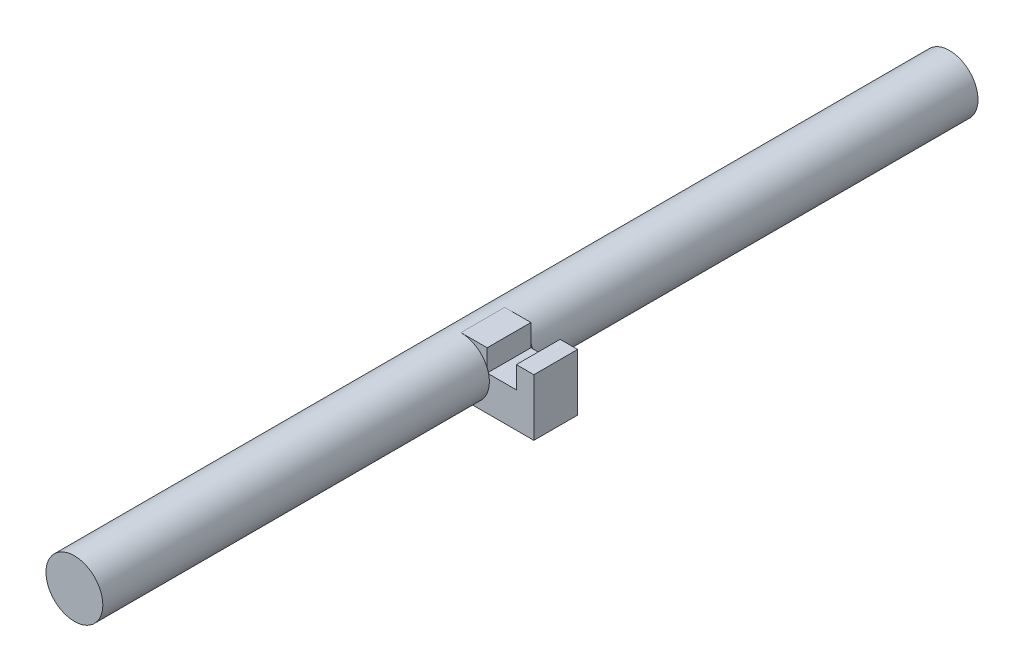
SolidWorks part; units mm, degrees
ref_plane "前视基准面" through (0, 0, 0) normal (0, 0, 1) x (1, 0, 0)
ref_plane "上视基准面" through (0, 0, 0) normal (0, 1, 0) x (1, 0, 0)
ref_plane "右视基准面" through (0, 0, 0) normal (1, 0, 0) x (0, 0, -1)
sketch "草图1" plane through (0, 0, 0) normal (0, 0, 1) x (1, 0, 0)
  circle A0 centre (0, 0) radius 1.95
  dimension "D1" = 3.9
extrude "凸台-拉伸1" add sketch "草图1" along normal blind 60
sketch "Sketch1" plane through (0, 0, 0) normal (1, 0, 0) x (0, 0, -1)
  line L0 (0, 1.95) -> (-60, 1.95) construction
  line L1 (-33.5, 1.95) -> (-30.5, 1.95)
  line L2 (-33.5, 1.95) -> (-33.5, -1.95)
  line L3 (-33.5, -1.95) -> (-30.5, -1.95)
  line L4 (-30.5, 1.95) -> (-30.5, -1.95)
  line L5 (-60, -1.95) -> (0, -1.95) construction
  line L6 (-60, 1.95) -> (-60, -1.95) construction
  dimension "D1" = 3
  dimension "D2" = 26.5
extrude "Boss-Extrude1" add sketch "Sketch1" along normal blind 5
sketch "Sketch2" plane through (0, 0, 30.5) normal (0, 0, -1) x (-1, 0, 0)
  line L0 (-5, 1.95) -> (0, 1.95) construction
  line L1 (-3.8, 1.95) -> (-1.8, 1.95)
  line L2 (-3.8, 1.95) -> (-3.8, 0.45)
  line L3 (-3.8, 0.45) -> (-1.8, 0.45)
  line L4 (-1.8, 1.95) -> (-1.8, 0.45)
  dimension "D1" = 1.5
  dimension "D2" = 2
  dimension "D3" = 1.2
extrude "Cut-Extrude1" cut sketch "Sketch2" against normal blind 3
